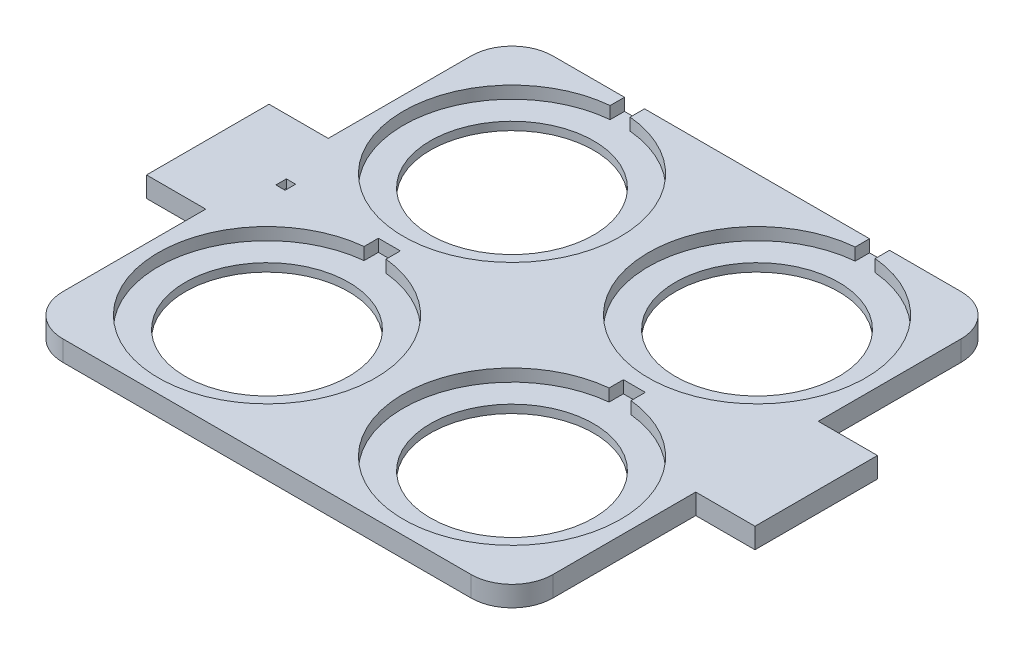
SolidWorks part; units mm, degrees
ref_plane "Front Plane" through (0, 0, 0) normal (0, 0, 1) x (1, 0, 0)
ref_plane "Top Plane" through (0, 0, 0) normal (0, 1, 0) x (1, 0, 0)
ref_plane "Right Plane" through (0, 0, 0) normal (1, 0, 0) x (0, 0, -1)
sketch "Sketch1" plane through (0, 0, 0) normal (0, 1, 0) x (1, 0, 0)
  line L1 (-60, 60) -> (60, 60)
  line L2 (-60, 60) -> (-60, -60)
  line L3 (-60, -60) -> (60, -60)
  line L4 (60, 60) -> (60, -60)
  line L5 (-60, 60) -> (60, -60) construction
  line L6 (-60, -60) -> (60, 60) construction
  point P0 (0, 0)
  dimension "D1" = 120
  dimension "D2" = 120
extrude "Boss-Extrude1" add sketch "Sketch1" along normal blind 5
sketch "Sketch2" plane through (0, 5, 0) normal (0, 1, 0) x (1, 0, 0)
  circle A0 centre (-30, 30) radius 20
  circle A2 centre (30, 30) radius 20
  circle A3 centre (30, -30) radius 20
  circle A4 centre (-30, -30) radius 20
  circle A5 centre (-30, 30) radius 26.6
  circle A6 centre (30, 30) radius 26.6
  circle A7 centre (30, -30) radius 26.6
  circle A8 centre (-30, -30) radius 26.6
  point P22 (0, 0)
  point P30 (0, 0)
  dimension "D1" = 40
  dimension "D3" = 53.2
  dimension "D2" = 4
  dimension "D4" = 4
extrude "Cut-Extrude4" cut sketch "Sketch2" against normal blind 5 contours A2 | A4 | A3 | A0
sketch "Sketch3" plane through (0, 5, 0) normal (0, 1, 0) x (1, 0, 0)
  circle A2 centre (-30, 30) radius 26.6
  circle A3 centre (30, 30) radius 26.6
  circle A4 centre (30, -30) radius 26.6
  circle A5 centre (-30, -30) radius 26.6
  point P16 (0, 0)
  circle M5 centre (30, -30) radius 20
  circle M6 centre (-30, -30) radius 20
  circle M7 centre (30, 30) radius 20
  dimension "D1" = 53.2
  dimension "D2" = 4
extrude "Cut-Extrude5" cut sketch "Sketch3" against normal blind 3 contours A3 M7 | A5 M6 | A4 M5 | A2
sketch "Sketch4" plane through (60, 0, 0) normal (1, 0, 0) x (0, 0, -1)
  line L0 (0, 0) -> (0, 5) construction
  line L1 (-60, 5) -> (60, 5) construction
  line L2 (-60, 0) -> (60, 0) construction
  line L3 (-30, 5) -> (30, 5)
  line L4 (-30, 5) -> (-30, 0)
  line L5 (-30, 0) -> (30, 0)
  line L6 (30, 5) -> (30, 0)
  line L7 (-30, 5) -> (30, 0) construction
  line L8 (-30, 0) -> (30, 5) construction
  point P5 (0, 2.5)
  dimension "D1" = 60
extrude "Boss-Extrude2" add sketch "Sketch4" along normal blind 14.5 contours L4 L3 L6 L5
sketch "Sketch5" plane through (-60, 0, 0) normal (-1, 0, 0) x (0, 0, 1)
  line L0 (0, 0) -> (0, 5) construction
  line L1 (-60, 5) -> (60, 5) construction
  line L2 (-60, 0) -> (60, 0) construction
  line L3 (-30, 5) -> (30, 5)
  line L4 (-30, 5) -> (-30, 0)
  line L5 (-30, 0) -> (30, 0)
  line L6 (30, 5) -> (30, 0)
  line L7 (-30, 5) -> (30, 0) construction
  line L8 (-30, 0) -> (30, 5) construction
  point P5 (0, 2.5)
  dimension "D1" = 60
extrude "Boss-Extrude3" add sketch "Sketch5" along normal blind 14.5
sketch "Sketch6" plane through (0, 5, 0) normal (0, 1, 0) x (1, 0, 0)
  line L1 (-74.5, 30) -> (-60, 30)
  line L2 (-74.5, 30) -> (-74.5, -30)
  line L3 (-74.5, -30) -> (-60, -30)
  line L4 (-60, 30) -> (-60, -30)
fillet "Fillet3" radius 10 1 edges at (-60, 2.5, 60)
fillet "Fillet4" radius 10 1 edges at (60, 2.5, 60)
fillet "Fillet5" radius 10 1 edges at (-60, 2.5, -60)
fillet "Fillet6" radius 10 1 edges at (60, 2.5, -60)
sketch "Sketch8" plane through (0, 5, 0) normal (0, 1, 0) x (1, 0, 0)
  line L2 (-60, 30) -> (-60, -30) construction
  line L3 (-74.5, 30) -> (-60, 30)
  line L4 (-74.5, 30) -> (-74.5, 15)
  line L5 (-74.5, 15) -> (-60, 15)
  line L6 (-60, 30) -> (-60, 15)
  line L7 (-74.5, 0) -> (74.5, 0) construction
  line L8 (-74.5, 30) -> (-74.5, -30) construction
  line L9 (74.5, -30) -> (74.5, 30) construction
  line L10 (-74.5, -15) -> (-60, -15)
  line L11 (-60, -30) -> (-60, -15)
  line L12 (-74.5, -30) -> (-60, -30)
  line L13 (-74.5, -30) -> (-74.5, -15)
  line L14 (0, 60) -> (0, -60) construction
  line L15 (50, 60) -> (-50, 60) construction
  line L16 (-50, -60) -> (50, -60) construction
  line L17 (74.5, -30) -> (74.5, -15)
  line L18 (74.5, -30) -> (60, -30)
  line L19 (60, -30) -> (60, -15)
  line L20 (74.5, -15) -> (60, -15)
  line L21 (74.5, 15) -> (60, 15)
  line L22 (60, 30) -> (60, 15)
  line L23 (74.5, 30) -> (60, 30)
  line L24 (74.5, 30) -> (74.5, 15)
  dimension "D1" = 15
sketch "Sketch10" plane through (0, 5, 0) normal (0, 1, 0) x (1, 0, 0)
  line L0 (0, 0) -> (-55.4064, 0) construction
  line L1 (-55.4064, -22.1211) -> (-55.4064, 0) construction
  line L3 (-56.5369, -1.2871) -> (-54.2758, -1.2871)
  line L4 (-56.5369, -1.2871) -> (-56.5369, 1.2871)
  line L5 (-56.5369, 1.2871) -> (-54.2758, 1.2871)
  line L6 (-54.2758, -1.2871) -> (-54.2758, 1.2871)
  line L7 (-56.5369, -1.2871) -> (-54.2758, 1.2871) construction
  line L8 (-56.5369, 1.2871) -> (-54.2758, -1.2871) construction
  circle A0 centre (-30, -30) radius 26.6 construction
  circle A1 centre (-30, -30) radius 26.6 construction
extrude "Cut-Extrude7" cut sketch "Sketch10" against normal blind 2
sketch "Sketch12" plane through (0, 5, 0) normal (0, 1, 0) x (1, 0, 0)
  line L0 (0, 60) -> (0, -60) construction
  line L1 (-32.6888, -0.0316) -> (-27.3112, -0.0316)
  line L2 (-32.6888, -0.0316) -> (-32.6888, -6.7684)
  line L3 (-32.6888, -6.7684) -> (-27.3112, -6.7684)
  line L4 (-27.3112, -0.0316) -> (-27.3112, -6.7684)
  line L5 (-32.6888, -0.0316) -> (-27.3112, -6.7684) construction
  line L6 (-32.6888, -6.7684) -> (-27.3112, -0.0316) construction
  line L7 (50, 60) -> (-50, 60) construction
  line L8 (-50, -60) -> (50, -60) construction
  line L9 (32.6888, -6.7684) -> (27.3112, -6.7684)
  line L10 (27.3112, -0.0316) -> (27.3112, -6.7684)
  line L11 (32.6888, -0.0316) -> (27.3112, -0.0316)
  line L12 (32.6888, -0.0316) -> (32.6888, -6.7684)
  circle A0 centre (-30, -30) radius 26.6 construction
  circle A1 centre (-30, -30) radius 26.6 construction
  point P0 (-30, -3.4)
extrude "Cut-Extrude10" cut sketch "Sketch12" against normal blind 3
sketch "Sketch14" plane through (0, 5, 0) normal (0, 1, 0) x (1, 0, 0)
  line L0 (-30, 56.6) -> (-30, 30) construction
  line L1 (0, 0) -> (0, 60) construction
  line L2 (-32.4513, 60.1213) -> (-27.5487, 60.1213)
  line L3 (-32.4513, 60.1213) -> (-32.4513, 53.0787)
  line L4 (-32.4513, 53.0787) -> (-27.5487, 53.0787)
  line L5 (-27.5487, 60.1213) -> (-27.5487, 53.0787)
  line L6 (-32.4513, 60.1213) -> (-27.5487, 53.0787) construction
  line L7 (-32.4513, 53.0787) -> (-27.5487, 60.1213) construction
  line L8 (50, 60) -> (-50, 60) construction
  line L9 (32.4513, 53.0787) -> (27.5487, 53.0787)
  line L10 (27.5487, 60.1213) -> (27.5487, 53.0787)
  line L11 (32.4513, 60.1213) -> (27.5487, 60.1213)
  line L12 (32.4513, 60.1213) -> (32.4513, 53.0787)
  circle A0 centre (-30, 30) radius 26.6 construction
  circle A1 centre (-30, 30) radius 26.6 construction
extrude "Cut-Extrude11" cut sketch "Sketch14" against normal blind 3
sketch "Sketch15" plane through (0, 5, 0) normal (0, 1, 0) x (1, 0, 0)
  line L0 (-60, 30) -> (-60, -30) construction
  line L1 (-74.5, 30) -> (-60, 30)
  line L2 (-74.5, 30) -> (-74.5, 15)
  line L3 (-74.5, 15) -> (-60, 15)
  line L4 (-60, 30) -> (-60, 15)
  line L5 (0, 60) -> (0, -60) construction
  line L6 (74.5, 15) -> (60, 15)
  line L7 (60, 30) -> (60, 15)
  line L8 (74.5, 30) -> (60, 30)
  line L9 (74.5, 30) -> (74.5, 15)
  line L10 (-74.5, 0) -> (74.5, 0) construction
  line L11 (74.5, -30) -> (74.5, -15)
  line L12 (74.5, -30) -> (60, -30)
  line L13 (60, -30) -> (60, -15)
  line L14 (74.5, -15) -> (60, -15)
  line L15 (-74.5, -15) -> (-60, -15)
  line L16 (-60, -30) -> (-60, -15)
  line L17 (-74.5, -30) -> (-60, -30)
  line L18 (-74.5, -30) -> (-74.5, -15)
  dimension "D1" = 15
extrude "Cut-Extrude12" cut sketch "Sketch15" against normal blind 10
